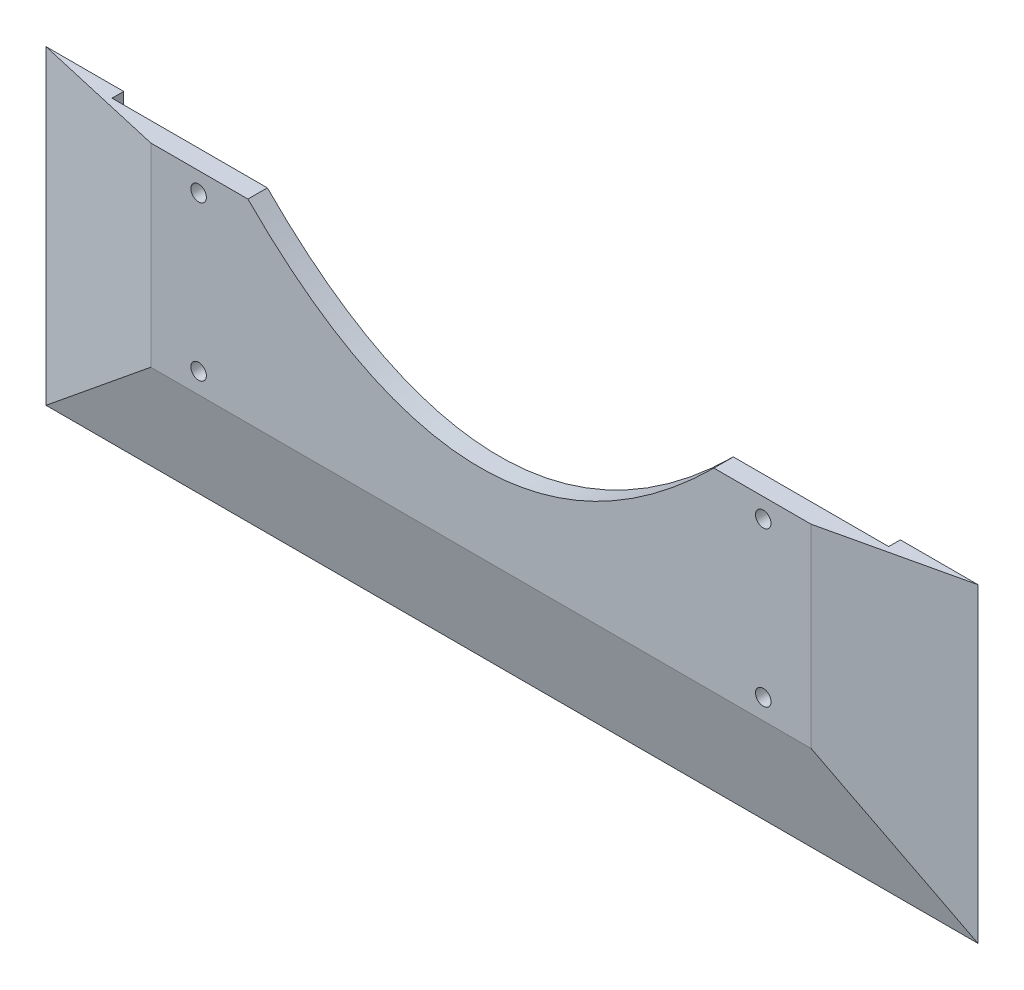
SolidWorks part; units mm, degrees
ref_plane "前视基准面" through (0, 0, 0) normal (0, 0, 1) x (1, 0, 0)
ref_plane "上视基准面" through (0, 0, 0) normal (0, 1, 0) x (1, 0, 0)
ref_plane "右视基准面" through (0, 0, 0) normal (1, 0, 0) x (0, 0, -1)
other "Configuration Table"
sketch "草图1" plane through (0, 0, 0) normal (0, 0, 1) x (1, 0, 0)
  line L1 (-100, 45) -> (100, 45)
  line L2 (-100, 45) -> (-100, -45)
  line L3 (-100, -45) -> (100, -45)
  line L4 (100, 45) -> (100, -45)
  line L5 (0, -45) -> (0, 45) construction
  line L6 (-100, 0) -> (100, 0) construction
  point P0 (0, 0)
  dimension "D1" = 200
  dimension "D2" = 90
extrude "凸台-拉伸1" add sketch "草图1" along normal blind 8
sketch "草图3" plane through (-100, 0, 0) normal (-1, 0, 0) x (0, 0, 1)
  line L0 (0, -45) -> (8, -15)
  line L1 (8, 45) -> (8, -45) construction
  line L2 (8, -15) -> (8, -45)
  line L4 (8, -45) -> (0, -45)
  dimension "D1" = 30
extrude "切除-拉伸2" cut sketch "草图3" against normal through all
sketch "草图7" plane through (0, 0, 0) normal (0, 0, -1) x (-1, 0, 0)
  line L0 (-100, -45) -> (-100, 45) construction
  line L1 (100, 45) -> (-100, 45)
  line L2 (100, 45) -> (100, 35)
  line L3 (100, 35) -> (-100, 35)
  line L4 (-100, 45) -> (-100, 35)
  dimension "D1" = 10
extrude "切除-拉伸6" cut sketch "草图7" against normal through all
sketch "草图8" plane through (0, 0, 0) normal (0, 0, -1) x (-1, 0, 0)
  line L0 (-100, 35) -> (100, 35) construction
  line L1 (100, 35) -> (100, -45) construction
  line L2 (-100, -45) -> (-100, 35) construction
  line L3 (60, 35) -> (-60, 35)
  spline S0 degree 2 poles (60, 35) (0.4615, -25.0142) (-60, 35) knots 0 0 0 1 1 1
  dimension "D1" = 40
  dimension "D2" = 40
  dimension "D3" = 30
extrude "切除-拉伸7" cut sketch "草图8" against normal through all
sketch "草图9" plane through (-100, 0, 0) normal (-1, 0, 0) x (0, 0, 1)
  line L4 (8, -15) -> (8, 35)
  line L5 (8, 35) -> (0, 35)
  line L6 (0, 35) -> (0, -45)
  line L7 (0, -45) -> (8, -15)
  line L8 (8, -15) -> (8, 35)
  line L9 (8, 35) -> (0, 35)
  line L10 (0, 35) -> (0, -45)
  line L11 (0, -45) -> (8, -15)
  dimension "D1" = 0
extrude "凸台-拉伸2" add sketch "草图9" along normal blind 20
sketch "草图10" plane through (100, 0, 0) normal (1, 0, 0) x (0, 0, -1)
  line L4 (0, -45) -> (0, 35)
  line L5 (0, 35) -> (-8, 35)
  line L6 (-8, 35) -> (-8, -15)
  line L7 (-8, -15) -> (0, -45)
  line L8 (0, -45) -> (0, 35)
  line L9 (0, 35) -> (-8, 35)
  line L10 (-8, 35) -> (-8, -15)
  line L11 (-8, -15) -> (0, -45)
  dimension "D1" = 0
extrude "凸台-拉伸3" add sketch "草图10" along normal blind 20
sketch "草图11" plane through (0, 35, 0) normal (0, 1, 0) x (1, 0, 0)
  line L0 (120, 0) -> (120, -8)
  line L1 (120, -8) -> (85, -8)
  line L2 (120, -8) -> (60, -8) construction
  line L3 (85, -8) -> (120, 0)
  line L4 (-120, 0) -> (-120, -8)
  line L5 (-120, -8) -> (-85, -8)
  line L6 (-60, -8) -> (-120, -8) construction
  line L7 (-85, -8) -> (-120, 0)
  dimension "D1" = 35
  dimension "D2" = 35
extrude "切除-拉伸8" cut sketch "草图11" against normal through all
sketch "草图12" plane through (0, 0, 8) normal (0, 0, 1) x (1, 0, 0)
  circle A0 centre (72.7, -9.7578) radius 2
  circle A1 centre (-72.7, -9.7578) radius 2
  circle A2 centre (72.7, 30) radius 2
  circle A3 centre (-72.7, 30) radius 2
extrude "切除-拉伸9" cut sketch "草图12" against normal through all
sketch "草图13" plane through (0, 0, 0) normal (0, 0, -1) x (-1, 0, 0)
  line L13 (-60, 35) -> (-100, 35)
  line L14 (-120, 35) -> (-60, 35) construction
  line L15 (-100, 35) -> (-100, -25)
  line L16 (-100, -25) -> (100, -25)
  line L17 (100, -25) -> (100, 35)
  line L18 (120, 35) -> (60, 35)
  line L19 (-60, 35) -> (-120, 35)
  line L20 (-120, 35) -> (-120, -45)
  line L21 (-120, -45) -> (120, -45)
  line L22 (120, -45) -> (120, 35)
  line L28 (60, 35) -> (120, 35) construction
  line L29 (100, 35) -> (60, 35)
  line L30 (-120, -45) -> (-120, 35) construction
  line L31 (120, 35) -> (120, -45) construction
  line L32 (120, -45) -> (-120, -45) construction
  parabola Q1 (60, 35) -> (-60, 35) focus (0.4614, 34.984) apex (0.692, 4.9947)
  parabola Q2 (60, 35) -> (-60, 35) focus (0.4614, 34.984) apex (0.692, 4.9947)
  dimension "D1" = 0
  dimension "D2" = 20
  dimension "D3" = 20
  dimension "D4" = 20
extrude "切除-拉伸10" cut sketch "草图13" against normal blind 3
